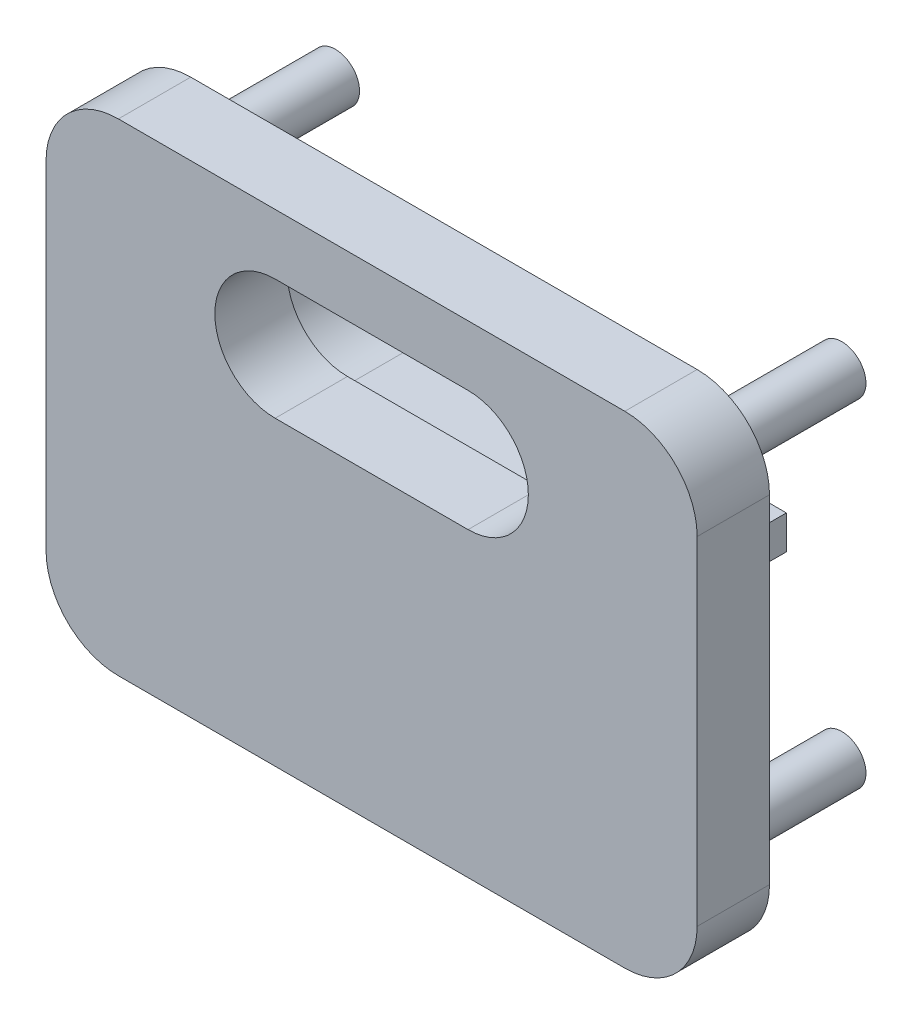
SolidWorks part; units mm, degrees
ref_plane "Front Plane" through (0, 0, 0) normal (0, 0, 1) x (1, 0, 0)
ref_plane "Top Plane" through (0, 0, 0) normal (0, 1, 0) x (1, 0, 0)
ref_plane "Right Plane" through (0, 0, 0) normal (1, 0, 0) x (0, 0, -1)
sketch "Sketch1" plane through (0, 0, 0) normal (0, 0, 1) x (1, 0, 0)
  line L0 (0, 20) -> (0, 0)
  line L1 (0, 0) -> (27, 0)
  line L3 (0, 20) -> (27, 20)
  line L5 (27, 20) -> (27, 0)
  line L6 (4, 17) -> (23, 17)
  line L8 (4, 3) -> (23, 3)
  line L10 (4, 16) -> (4, 4)
  line L12 (23, 16) -> (23, 4)
  line L14 (4, 16) -> (4, 17)
  line L15 (4, 4) -> (4, 3)
  line L16 (23, 16) -> (23, 17)
  line L17 (23, 4) -> (23, 3)
  line L19 (4, 16) -> (23, 16) construction
  line L20 (4, 4) -> (23, 4) construction
  line L21 (3, 17) -> (3, 3) construction
  line L22 (3, 17) -> (24, 17) construction
  line L23 (3, 3) -> (24, 3) construction
  line L24 (24, 17) -> (24, 3) construction
  dimension "D1" = 20
  dimension "D2" = 27
  dimension "D3" = 3
  dimension "D4" = 4
extrude "Boss-Extrude1" add sketch "Sketch1" against normal blind 50
sketch "Sketch2" plane through (0, 0, -50) normal (0, 0, -1) x (-1, 0, 0)
  line L1 (-23, 17) -> (-4, 17)
  line L2 (-23, 17) -> (-23, 3)
  line L3 (-23, 3) -> (-4, 3)
  line L4 (-4, 17) -> (-4, 3)
extrude "Boss-Extrude2" add sketch "Sketch2" against normal blind 2
sketch "Sketch3" plane through (0, 0, 0) normal (0, 0, 1) x (1, 0, 0)
  line L0 (13.5, 14) -> (13.5, 12) construction
  line L1 (2, 14) -> (25, 14)
  line L2 (2, 14) -> (2, 12)
  line L3 (2, 12) -> (25, 12)
  line L4 (25, 14) -> (25, 12)
  line L5 (13.5, 20) -> (13.5, 18.1622) construction
  line L6 (27, 20) -> (0, 20) construction
  line L7 (27, 0) -> (27, 20) construction
  dimension "D1" = 6
  dimension "D2" = 2
  dimension "D3" = 2
extrude "Cut-Extrude1" cut sketch "Sketch3" against normal up to surface (48 mm away) up to face at (13.5, 10, -48)
sketch "Sketch4" plane through (0, 0, 0) normal (0, 0, 1) x (1, 0, 0)
  line L0 (4, 3) -> (23, 3) construction
  line L1 (4, 12) -> (4.5, 12)
  line L2 (4, 12) -> (4, 3)
  line L3 (4, 3) -> (4.5, 3)
  line L4 (4.5, 12) -> (4.5, 3)
  line L5 (23, 14) -> (23, 17) construction
  line L6 (23, 12) -> (22.5, 12)
  line L7 (23, 12) -> (23, 3)
  line L8 (23, 3) -> (22.5, 3)
  line L9 (22.5, 12) -> (22.5, 3)
  line L10 (4, 17) -> (23, 17)
  line L11 (4, 17) -> (4, 16.5)
  line L12 (4, 16.5) -> (23, 16.5)
  line L13 (23, 17) -> (23, 16.5)
  dimension "D1" = 0.5
  dimension "D2" = 0.5
  dimension "D3" = 0.5
extrude "Boss-Extrude3" add sketch "Sketch4" against normal up to surface (48 mm away)
fillet "Fillet1" radius 3 4 edges at (27, 0, -25) (27, 20, -25) (0, 0, -25) (0, 20, -25)
sketch "Sketch5" plane through (0, 0, 0) normal (0, 0, 1) x (1, 0, 0)
  line L8 (3, 0) -> (24, 0)
  line L9 (27, 3) -> (27, 17)
  line L10 (24, 20) -> (3, 20)
  line L11 (0, 17) -> (0, 3)
  line L12 (3, 0) -> (24, 0)
  line L13 (27, 3) -> (27, 17)
  line L14 (24, 20) -> (3, 20)
  line L15 (0, 17) -> (0, 3)
  line L17 (4, 14) -> (4, 16.5)
  line L18 (4, 16.5) -> (23, 16.5)
  line L19 (4, 14) -> (4, 16.5)
  line L20 (4, 16.5) -> (23, 16.5)
  line L43 (23, 14) -> (23, 16.5)
  line L44 (23, 16.5) -> (4, 16.5)
  line L45 (4, 16.5) -> (4, 14)
  line L46 (4, 14) -> (2, 14)
  line L47 (2, 14) -> (2, 12)
  line L48 (2, 12) -> (4.5, 12)
  line L49 (4.5, 12) -> (4.5, 3)
  line L50 (4.5, 3) -> (22.5, 3)
  line L51 (22.5, 3) -> (22.5, 12)
  line L52 (22.5, 12) -> (25, 12)
  line L53 (25, 12) -> (25, 14)
  line L54 (25, 14) -> (23, 14)
  line L55 (23, 14) -> (23, 16.5)
  line L56 (23, 16.5) -> (4, 16.5)
  line L57 (4, 16.5) -> (4, 14)
  line L58 (4, 14) -> (2, 14)
  line L59 (2, 14) -> (2, 12)
  line L60 (2, 12) -> (4.5, 12)
  line L61 (4.5, 12) -> (4.5, 3)
  line L62 (4.5, 3) -> (22.5, 3)
  line L63 (22.5, 3) -> (22.5, 12)
  line L64 (22.5, 12) -> (25, 12)
  line L65 (25, 12) -> (25, 14)
  line L66 (25, 14) -> (23, 14)
  arc A8 (24, 0) -> (27, 3) centre (24, 3) ccw
  arc A9 (27, 17) -> (24, 20) centre (24, 17) ccw
  arc A10 (3, 20) -> (0, 17) centre (3, 17) ccw
  arc A11 (0, 3) -> (3, 0) centre (3, 3) ccw
  arc A12 (24, 0) -> (27, 3) centre (24, 3) ccw
  arc A13 (27, 17) -> (24, 20) centre (24, 17) ccw
  arc A14 (3, 20) -> (0, 17) centre (3, 17) ccw
  arc A15 (0, 3) -> (3, 0) centre (3, 3) ccw
  line M23 (22.5, 3) -> (4.5, 3)
  line M24 (4.5, 3) -> (4.5, 12)
  line M25 (4.5, 12) -> (2, 12)
  line M26 (2, 12) -> (2, 14)
  line M27 (2, 14) -> (4, 14)
  line M28 (4, 14) -> (4, 16.5)
  line M29 (4, 16.5) -> (23, 16.5)
  line M30 (23, 16.5) -> (23, 14)
  line M31 (23, 14) -> (25, 14)
  line M32 (25, 14) -> (25, 12)
  line M33 (25, 12) -> (22.5, 12)
  line M34 (22.5, 12) -> (22.5, 3)
  dimension "D1" = 0
  dimension "D2" = 0
  dimension "D3" = 0
sketch "Sketch7" plane through (27, 0, 0) normal (1, 0, 0) x (0, 0, -1)
  line L0 (0, 20) -> (50, 20) construction
  line L1 (50, 0) -> (3, 0)
  line L2 (50, 0) -> (50, 20)
  line L3 (50, 20) -> (3, 20)
  line L4 (3, 0) -> (3, 20)
  line L5 (0, 20) -> (0, 17) construction
  dimension "D1" = 3
extrude "Cut-Extrude6" cut sketch "Sketch7" against normal up to next
extrude "Boss-Extrude5" add sketch "Sketch5" against normal blind 6 contours M23 M34 M33 M32 M31 M30 M29 M28 M27 M26 M25 M24
sketch "Sketch8" plane through (0, 0, -6) normal (0, 0, -1) x (-1, 0, 0)
  line L0 (-17.5, 15) -> (-9.5, 15) construction
  line L2 (-17.5, 17.5) -> (-9.5, 17.5)
  line L3 (-17.5, 12.5) -> (-9.5, 12.5)
  line L4 (-13.5, 3) -> (-13.5, 30) construction
  line L5 (-22.5, 3) -> (-4.5, 3) construction
  line L8 (-3, 20) -> (-24, 20) construction
  arc A0 (-17.5, 17.5) -> (-17.5, 12.5) centre (-17.5, 15) ccw
  arc A1 (-9.5, 12.5) -> (-9.5, 17.5) centre (-9.5, 15) ccw
  point P4 (-13.5, 15)
  dimension "D2" = 8
  dimension "D1" = 5
  dimension "D3" = 5
extrude "Cut-Extrude7" cut sketch "Sketch8" against normal up to next
sketch "Sketch9" plane through (0, 0, -3) normal (0, 0, -1) x (-1, 0, 0)
  circle A0 centre (-24, 17) radius 1
  circle A1 centre (-3, 17) radius 1
  circle A2 centre (-3, 3) radius 1
  circle A3 centre (-24, 3) radius 1
  dimension "D1" = 2
  dimension "D2" = 2
  dimension "D3" = 2
  dimension "D4" = 2
extrude "Boss-Extrude6" add sketch "Sketch9" along normal blind 6
sketch "Sketch11" plane through (0, 0, -6) normal (0, 0, -1) x (-1, 0, 0)
  line L28 (-19.5, 16.5) -> (-23, 16.5)
  line L29 (-23, 16.5) -> (-23, 14)
  line L30 (-23, 14) -> (-25, 14)
  line L31 (-25, 14) -> (-25, 12)
  line L32 (-25, 12) -> (-22.5, 12)
  line L33 (-22.5, 12) -> (-22.5, 3)
  line L34 (-22.5, 3) -> (-4.5, 3)
  line L35 (-4.5, 3) -> (-4.5, 12)
  line L36 (-4.5, 12) -> (-2, 12)
  line L37 (-2, 12) -> (-2, 14)
  line L38 (-2, 14) -> (-4, 14)
  line L39 (-4, 14) -> (-4, 16.5)
  line L40 (-4, 16.5) -> (-7.5, 16.5)
  line L42 (-2, 14) -> (-4, 14)
  line L43 (-17.5, 12.5) -> (-9.5, 12.5)
  line L44 (-17.5, 12.5) -> (-9.5, 12.5)
  line L45 (-4, 14) -> (-4, 16.5)
  line L46 (-4, 16.5) -> (-7.5, 16.5)
  line L47 (-17.5, 12.5) -> (-9.5, 12.5)
  line L48 (-19.5, 16.5) -> (-23, 16.5)
  line L49 (-20.0298, 16.2) -> (-22.7, 16.2)
  line L50 (-22.7, 16.2) -> (-22.7, 13.7)
  line L51 (-22.7, 13.7) -> (-24.7, 13.7)
  line L52 (-24.7, 13.7) -> (-24.7, 12.3)
  line L53 (-24.7, 12.3) -> (-22.2, 12.3)
  line L54 (-22.2, 12.3) -> (-22.2, 3.3)
  line L55 (-22.2, 3.3) -> (-4.8, 3.3)
  line L56 (-4.8, 3.3) -> (-4.8, 12.3)
  line L57 (-4.8, 12.3) -> (-2.3, 12.3)
  line L58 (-2.3, 12.3) -> (-2.3, 13.7)
  line L59 (-2.3, 13.7) -> (-4.3, 13.7)
  line L60 (-4.3, 13.7) -> (-4.3, 16.2)
  line L61 (-4.3, 16.2) -> (-6.9702, 16.2)
  line L62 (-17.5, 12.2) -> (-9.5, 12.2)
  arc A13 (-19.5, 16.5) -> (-17.5, 12.5) centre (-17.5, 15) ccw
  arc A14 (-19.5, 16.5) -> (-17.5, 12.5) centre (-17.5, 15) ccw
  arc A15 (-9.5, 12.5) -> (-7.5, 16.5) centre (-9.5, 15) ccw
  arc A16 (-9.5, 12.5) -> (-7.5, 16.5) centre (-9.5, 15) ccw
  arc A17 (-9.5, 12.5) -> (-7.5, 16.5) centre (-9.5, 15) ccw
  arc A18 (-19.5, 16.5) -> (-17.5, 12.5) centre (-17.5, 15) ccw
  arc A19 (-9.5, 12.2) -> (-6.9702, 16.2) centre (-9.5, 15) ccw
  arc A20 (-20.0298, 16.2) -> (-17.5, 12.2) centre (-17.5, 15) ccw
  line M10 (-9.5, 12.5) -> (-17.5, 12.5)
  arc M11 (-17.5, 12.5) -> (-19.5, 16.5) centre (-17.5, 15) cw
  line M12 (-19.5, 16.5) -> (-23, 16.5)
  line M13 (-23, 16.5) -> (-23, 14)
  line M14 (-23, 14) -> (-25, 14)
  line M15 (-25, 14) -> (-25, 12)
  line M16 (-25, 12) -> (-22.5, 12)
  line M17 (-22.5, 12) -> (-22.5, 3)
  line M18 (-22.5, 3) -> (-4.5, 3)
  line M19 (-4.5, 3) -> (-4.5, 12)
  line M20 (-4.5, 12) -> (-2, 12)
  line M21 (-2, 12) -> (-2, 14)
  line M22 (-2, 14) -> (-4, 14)
  line M23 (-4, 14) -> (-4, 16.5)
  line M24 (-4, 16.5) -> (-7.5, 16.5)
  arc M25 (-7.5, 16.5) -> (-9.5, 12.5) centre (-9.5, 15) cw
  dimension "D1" = 0
  dimension "D2" = 0
  dimension "D3" = 0
  dimension "D4" = 0
  dimension "D5" = 0.3
extrude "Cut-Extrude8" cut sketch "Sketch11" against normal up to surface (3 mm away) contours L49 A20 L62 A19 L61 L60 L59 L58 L57 L56 L55 L54 L53 L52 L51 L50 M25 M10 M11 M12 M13 M14 M15 M16 M17 M18 M19 M20 M21 M22 M23 M24 up to face at (24, 2, -3)
